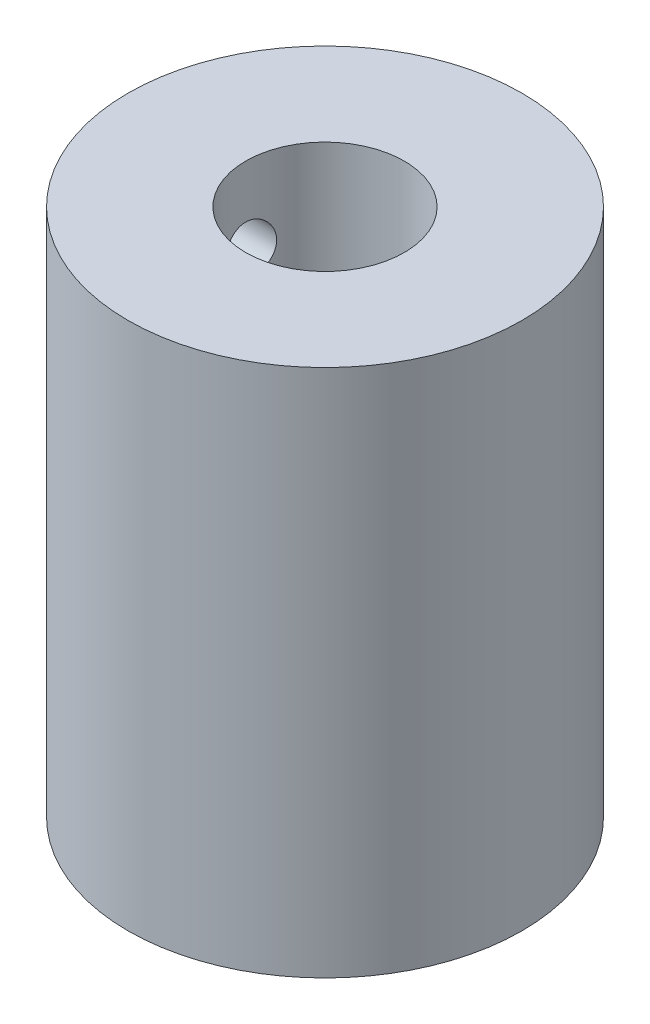
SolidWorks part; units mm, degrees
ref_plane "Front Plane" through (0, 0, 0) normal (0, 0, 1) x (1, 0, 0)
ref_plane "Top Plane" through (0, 0, 0) normal (0, 1, 0) x (1, 0, 0)
ref_plane "Right Plane" through (0, 0, 0) normal (1, 0, 0) x (0, 0, -1)
sketch "Sketch1" plane through (0, 0, 0) normal (0, 1, 0) x (1, 0, 0)
  circle A0 centre (0, 0) radius 7.45
  dimension "D1" = 14.9
extrude "Boss-Extrude1" add sketch "Sketch1" along normal blind 20
sketch "Sketch2" plane through (0, 20, 0) normal (0, 1, 0) x (1, 0, 0)
  circle A0 centre (0, 0) radius 3
  dimension "D1" = 6
extrude "Cut-Extrude1" cut sketch "Sketch2" against normal blind 14
sketch "Sketch3" plane through (0, 0, 0) normal (0, -1, 0) x (1, 0, 0)
  circle A0 centre (0, 0) radius 2.5
  dimension "D1" = 5
extrude "Cut-Extrude2" cut sketch "Sketch3" against normal blind 6
sketch "Sketch4" plane through (0, 0, 0) normal (1, 0, 0) x (0, 0, -1)
  line L0 (3, 20) -> (-3, 20) construction
  line L1 (0, 20) -> (0, 0) construction
  line L2 (7.45, 20) -> (-7.45, 20) construction
  line L3 (-7.45, 10) -> (7.45, 10) construction
  line L4 (-7.45, 20) -> (-7.45, 0) construction
  line L5 (7.45, 0) -> (7.45, 20) construction
  circle A0 centre (0, 17) radius 1
  point P15 (1.2237, 17)
  dimension "D2" = 2
  dimension "D1" = 3
extrude "Cut-Extrude3" cut sketch "Sketch4" against normal up to surface (7.3826 mm away)
sketch "Sketch6" plane through (0, 0, 0) normal (0, 0, 1) x (1, 0, 0)
  line L0 (0, 20) -> (0, 0) construction
  line L1 (3, 20) -> (-3, 20) construction
  line L2 (-7.45, 0) -> (7.45, 0) construction
  circle A0 centre (0, 3) radius 1
  dimension "D1" = 2
  dimension "D2" = 3
extrude "Cut-Extrude4" cut sketch "Sketch6" against normal up to surface (7.3826 mm away)
